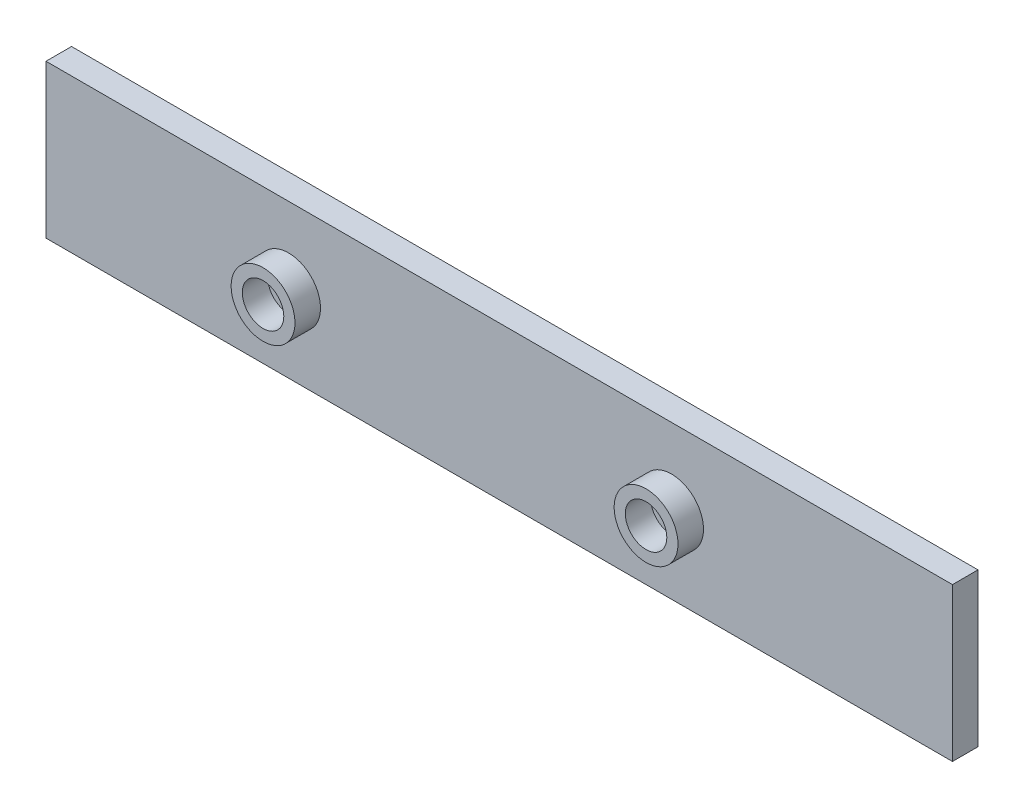
SolidWorks part; units mm, degrees
ref_plane "Front Plane" through (0, 0, 0) normal (0, 0, 1) x (1, 0, 0)
ref_plane "Top Plane" through (0, 0, 0) normal (0, 1, 0) x (1, 0, 0)
ref_plane "Right Plane" through (0, 0, 0) normal (1, 0, 0) x (0, 0, -1)
sketch "Sketch1" plane through (0, 0, 0) normal (0, 0, 1) x (1, 0, 0)
  line L1 (0, 0) -> (71, 0)
  line L2 (0, 0) -> (0, 12)
  line L3 (0, 12) -> (71, 12)
  line L4 (71, 0) -> (71, 12)
  dimension "D1" = 12
  dimension "D2" = 71
extrude "Boss-Extrude1" add sketch "Sketch1" along normal blind 2
sketch "Sketch2" plane through (0, 0, 2) normal (0, 0, 1) x (1, 0, 0)
  line L0 (0, 12) -> (0, 0) construction
  circle A0 centre (19, 6) radius 1.625
  circle A1 centre (49, 6) radius 1.625
  circle A2 centre (19, 6) radius 2.5
  circle A3 centre (49, 6) radius 2.5
  point P8 (0, 6)
  dimension "D1" = 3.25
  dimension "D2" = 19
  dimension "D4" = 5
  dimension "D3" = 30
extrude "Boss-Extrude2" add sketch "Sketch2" along normal blind 2
